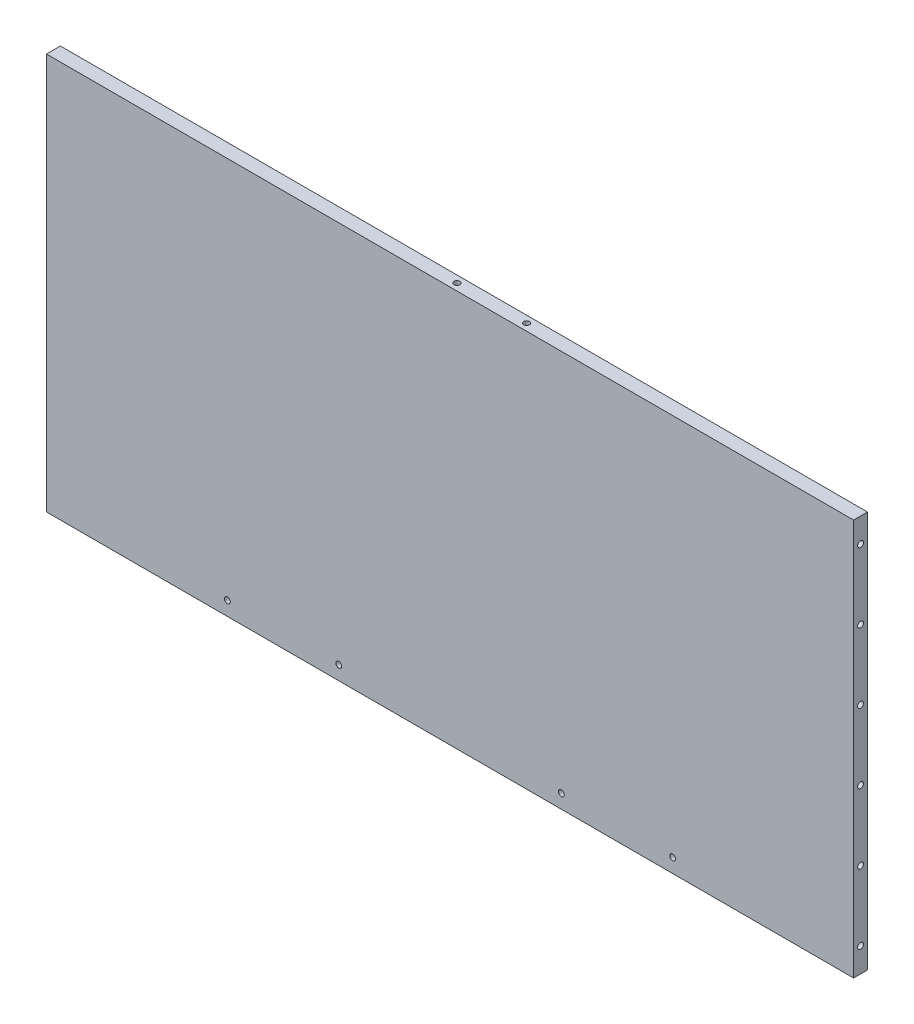
SolidWorks part; units mm, degrees
material "1.4511 (X3CrNb17)"
ref_plane "前视基准面" through (0, 0, 0) normal (0, 0, 1) x (1, 0, 0)
ref_plane "上视基准面" through (0, 0, 0) normal (0, 1, 0) x (1, 0, 0)
ref_plane "右视基准面" through (0, 0, 0) normal (1, 0, 0) x (0, 0, -1)
sketch "草图1" plane through (0, 0, 0) normal (0, 0, 1) x (1, 0, 0)
  line L1 (-290, 142.5) -> (290, 142.5)
  line L2 (-290, 142.5) -> (-290, -142.5)
  line L3 (-290, -142.5) -> (290, -142.5)
  line L4 (290, 142.5) -> (290, -142.5)
  line L5 (-290, 142.5) -> (290, -142.5) construction
  line L6 (-290, -142.5) -> (290, 142.5) construction
  point P0 (0, 0)
  dimension "D1" = 580
  dimension "D2" = 285
extrude "凸台-拉伸1" add sketch "草图1" along normal blind 10
sketch "草图2" plane through (290, 0, 0) normal (1, 0, 0) x (0, 0, -1)
  line L0 (-10, 142.5) -> (0, 142.5) construction
  point P0 (-5, 125)
  point P3 (-5, 75)
  point P5 (-5, 25)
  point P6 (-5, -25)
  point P7 (-5, -75)
  point P8 (-5, -125)
  dimension "D1" = 17.5
  dimension "D2" = 6
hole_wizard "M5 螺纹孔1" positions "草图3" profile "草图4" tap size "M5" standard "GB" end condition through all
sketch "草图3" plane through (290, 0, 0) normal (1, 0, 0) x (0, 0, -1)
  point P0 (-5, 125)
  point P3 (-5, 75)
  point P6 (-5, 25)
  point P9 (-5, -25)
  point P12 (-5, -75)
  point P15 (-5, -125)
cosmetic thread "孔螺蚊线1" parameters "D2"=5
cosmetic thread "孔螺蚊线2" parameters "D2"=5
cosmetic thread "孔螺蚊线3" parameters "D2"=5
cosmetic thread "孔螺蚊线4" parameters "D2"=5
cosmetic thread "孔螺蚊线5" parameters "D2"=5
cosmetic thread "孔螺蚊线6" parameters "D2"=5
sketch "草图4" plane through (290, 125, 5) normal (0, 1, 0) x (0, 0, -1)
  line L0 (0, 0) -> (0, 580)
  line L1 (0, 580) -> (2.1, 580)
  line L2 (2.1, 580) -> (2.1, 0)
  line L5 (2.1, 0) -> (0, 0)
  line L11 (0, -6.35) -> (0, 107.95) construction
  dimension "通孔螺纹孔钻头直径" = 4.2
  dimension "通孔螺纹孔钻头深度" = 580
sketch "草图5" plane through (0, 142.5, 0) normal (0, 1, 0) x (1, 0, 0)
  line L0 (-290, -10) -> (-290, 0) construction
  point P0 (-290, -5)
  point P1 (0, -5)
  point P6 (50, -5)
  dimension "D1" = 290
  dimension "D2" = 2
hole_wizard "M5 螺纹孔2" positions "草图6" profile "草图7" tap size "M5" standard "GB" end condition through all
sketch "草图6" plane through (0, 142.5, 0) normal (0, 1, 0) x (1, 0, 0)
  point P0 (0, -5)
  point P3 (50, -5)
sketch "草图7" plane through (0, 142.5, 5) normal (1, 0, 0) x (0, 0, 1)
  line L0 (0, 0) -> (0, 285)
  line L1 (0, 285) -> (2.1, 285)
  line L2 (2.1, 285) -> (2.1, 0)
  line L5 (2.1, 0) -> (0, 0)
  line L11 (0, -6.35) -> (0, 107.95) construction
  dimension "通孔螺纹孔钻头直径" = 4.2
  dimension "通孔螺纹孔钻头深度" = 285
cosmetic thread "孔螺蚊线7" parameters "D2"=5
cosmetic thread "孔螺蚊线8" parameters "D2"=5
sketch "草图8" plane through (0, 0, 10) normal (0, 0, 1) x (1, 0, 0)
  line L0 (-160, -132.5) -> (160, -132.5) construction
  line L1 (-290, -142.5) -> (290, -142.5) construction
  line L2 (0, 0) -> (0, -142.5) construction
  line L3 (-80, -132.5) -> (80, -132.5) construction
  point P7 (0, -132.5)
  point P10 (0, -132.5)
  dimension "D1" = 320
  dimension "D2" = 10
  dimension "D3" = 160
  dimension "D4" = 10
hole_wizard "M5 螺纹孔3" positions "草图9" profile "草图10" tap size "M5" standard "GB" end condition through all
sketch "草图9" plane through (0, 0, 10) normal (0, 0, 1) x (1, 0, 0)
  point P0 (-160, -132.5)
  point P3 (-80, -132.5)
  point P6 (80, -132.5)
  point P9 (160, -132.5)
cosmetic thread "孔螺蚊线9" parameters "D2"=5
cosmetic thread "孔螺蚊线10" parameters "D2"=5
cosmetic thread "孔螺蚊线11" parameters "D2"=5
cosmetic thread "孔螺蚊线12" parameters "D2"=5
sketch "草图10" plane through (-160, -132.5, 10) normal (1, 0, 0) x (0, -1, 0)
  line L0 (0, 0) -> (0, 10)
  line L1 (0, 10) -> (2.1, 10)
  line L2 (2.1, 10) -> (2.1, 0)
  line L5 (2.1, 0) -> (0, 0)
  line L11 (0, -6.35) -> (0, 107.95) construction
  dimension "通孔螺纹孔钻头直径" = 4.2
  dimension "通孔螺纹孔钻头深度" = 10
sketch "草图11" plane through (0, 0, 0) normal (0, 0, -1) x (-1, 0, 0)
  line L0 (-290, 142.5) -> (290, 142.5) construction
  line L1 (-165, 127.5) -> (165, 127.5)
  line L2 (-165, 127.5) -> (-165, 47.5)
  line L3 (-165, 47.5) -> (165, 47.5)
  line L4 (165, 127.5) -> (165, 47.5)
  line L5 (-165, 127.5) -> (165, 47.5) construction
  line L6 (-165, 47.5) -> (165, 127.5) construction
  line L7 (-290, -142.5) -> (-290, 142.5) construction
  point P0 (0, 87.5)
  dimension "D1" = 330
  dimension "D2" = 80
  dimension "D3" = 15
  dimension "D4" = 125
extrude "切除-拉伸1" cut sketch "草图11" against normal blind 2
sketch "草图12" plane through (0, 0, 2) normal (0, 0, -1) x (-1, 0, 0)
  line L1 (-155, 119.5) -> (155, 119.5) construction
  line L2 (-155, 119.5) -> (-155, 55.5) construction
  line L3 (-155, 55.5) -> (155, 55.5) construction
  line L4 (155, 119.5) -> (155, 55.5) construction
  line L5 (-155, 119.5) -> (155, 55.5) construction
  line L6 (-155, 55.5) -> (155, 119.5) construction
  point P0 (0, 87.5)
  dimension "D1" = 310
  dimension "D2" = 64
hole_wizard "M5 螺纹孔4" positions "草图13" profile "草图14" tap size "M5" standard "GB"
sketch "草图13" plane through (0, 0, 2) normal (0, 0, -1) x (-1, 0, 0)
  point P0 (-155, 119.5)
  point P3 (-155, 55.5)
  point P6 (155, 55.5)
  point P9 (155, 119.5)
cosmetic thread "孔螺蚊线13" parameters "D2"=5
cosmetic thread "孔螺蚊线14" parameters "D2"=5
cosmetic thread "孔螺蚊线15" parameters "D2"=5
cosmetic thread "孔螺蚊线16" parameters "D2"=5
sketch "草图14" plane through (155, 119.5, 2) normal (1, 0, 0) x (0, 1, 0)
  line L0 (0, 0) -> (0, 3.2618)
  line L1 (0, 3.2618) -> (2.1, 2)
  line L2 (2.1, 2) -> (2.1, 0)
  line L5 (2.1, 0) -> (0, 0)
  line L10 (0, 3.2618) -> (-2.1, 2) construction
  line L11 (0, -6.35) -> (0, 107.95) construction
  dimension "螺纹孔钻头直径" = 4.2
  dimension "螺纹孔钻头深度" = 2
  dimension "导头角度" = 118
